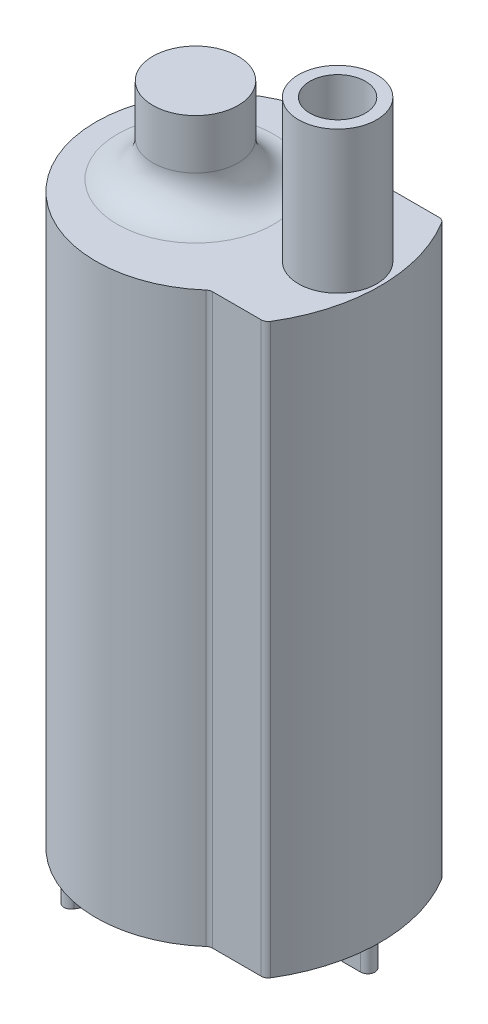
SolidWorks part; units mm, degrees
ref_plane "Front Plane" through (0, 0, 0) normal (0, 0, 1) x (1, 0, 0)
ref_plane "Top Plane" through (0, 0, 0) normal (0, 1, 0) x (1, 0, 0)
ref_plane "Right Plane" through (0, 0, 0) normal (1, 0, 0) x (0, 0, -1)
sketch "Sketch1" plane through (0, 0, 0) normal (0, 1, 0) x (1, 0, 0)
  line L0 (11.5217, 12.5) -> (19.3067, 12.5)
  line L2 (19.3067, -12.5) -> (11.5217, -12.5)
  arc A0 (11.5217, 12.5) -> (11.5217, -12.5) centre (0, 0) ccw
  arc A1 (19.3067, -12.5) -> (19.3067, 12.5) centre (0, 0) ccw
  point P1 (-17, 0)
  point P3 (23, 0)
  dimension "D1" = 17
  dimension "D2" = 25
  dimension "D3" = 40
extrude "Boss-Extrude1" add sketch "Sketch1" along normal blind 80
sketch "Sketch2" plane through (0, 80, 0) normal (0, 1, 0) x (1, 0, 0)
  circle A0 centre (17, 0) radius 5.5
  circle A1 centre (17, 0) radius 3.9
  dimension "D2" = 11
  dimension "D3" = 1.6
  dimension "D1" = 17
extrude "Boss-Extrude2" add sketch "Sketch2" along normal blind 20
sketch "Sketch3" plane through (0, 80, 0) normal (0, 1, 0) x (1, 0, 0)
  circle A0 centre (-3, 0) radius 6
  dimension "D1" = 12
  dimension "D2" = 3
extrude "Boss-Extrude3" add sketch "Sketch3" along normal blind 12
fillet "Fillet1" radius 5 1 edges at (-3, 80, 6)
sketch "Sketch4" plane through (0, 0, 0) normal (0, -1, 0) x (1, 0, 0)
  line L0 (0, 0) -> (-12.7825, 22.1399) construction
  line L1 (0, 0) -> (-12.8284, -22.2195) construction
  line L2 (0, 0) -> (29.9508, 0) construction
  line L3 (-6.25, 10.8253) -> (-7.5, 12.9904) construction
  line L4 (-7.116, 10.3253) -> (-8.366, 12.4904)
  line L5 (-5.384, 11.3253) -> (-6.634, 13.4904)
  line L6 (-6.25, -10.8253) -> (-7.5, -12.9904) construction
  line L7 (-5.384, -11.3253) -> (-6.634, -13.4904)
  line L8 (-7.116, -10.3253) -> (-8.366, -12.4904)
  line L9 (18.75, 0) -> (21.25, 0) construction
  line L10 (18.75, 1) -> (21.25, 1)
  line L11 (18.75, -1) -> (21.25, -1)
  arc A0 (-7.116, 10.3253) -> (-5.384, 11.3253) centre (-6.25, 10.8253) ccw
  arc A1 (-6.634, 13.4904) -> (-8.366, 12.4904) centre (-7.5, 12.9904) ccw
  arc A2 (-5.384, -11.3253) -> (-7.116, -10.3253) centre (-6.25, -10.8253) ccw
  arc A3 (-8.366, -12.4904) -> (-6.634, -13.4904) centre (-7.5, -12.9904) ccw
  arc A4 (18.75, 1) -> (18.75, -1) centre (18.75, 0) ccw
  arc A5 (21.25, -1) -> (21.25, 1) centre (21.25, 0) ccw
  arc A6 (11.5217, 12.5) -> (11.5217, -12.5) centre (0, 0) ccw construction
  point P7 (-6.875, 11.9078)
  point P13 (-6.875, -11.9078)
  point P20 (20, 0)
  dimension "D1" = 120
  dimension "D2" = 120
  dimension "D3" = 2
  dimension "D4" = 2.5
  dimension "D5" = 15
  dimension "D6" = 15
  dimension "D7" = 20
extrude "Boss-Extrude4" add sketch "Sketch4" along normal blind 4
fillet "Fillet2" radius 1 4 edges at (19.3067, 40, -12.5) (11.5217, 40, -12.5) (19.3067, 40, 12.5) (11.5217, 40, 12.5)
